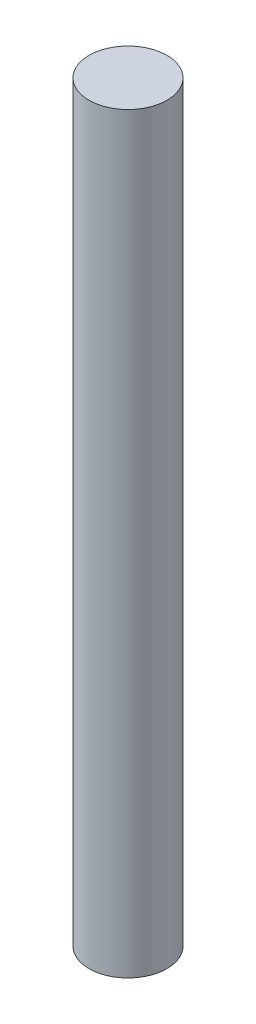
SolidWorks part; units mm, degrees
ref_plane "Front Plane" through (0, 0, 0) normal (0, 0, 1) x (1, 0, 0)
ref_plane "Top Plane" through (0, 0, 0) normal (0, 1, 0) x (1, 0, 0)
ref_plane "Right Plane" through (0, 0, 0) normal (1, 0, 0) x (0, 0, -1)
sketch "Sketch1" plane through (0, 0, 0) normal (0, 1, 0) x (1, 0, 0)
  circle A0 centre (0, 0) radius 1.1906
  dimension "D1" = 2.3813
extrude "Boss-Extrude1" add sketch "Sketch1" along normal blind 23
